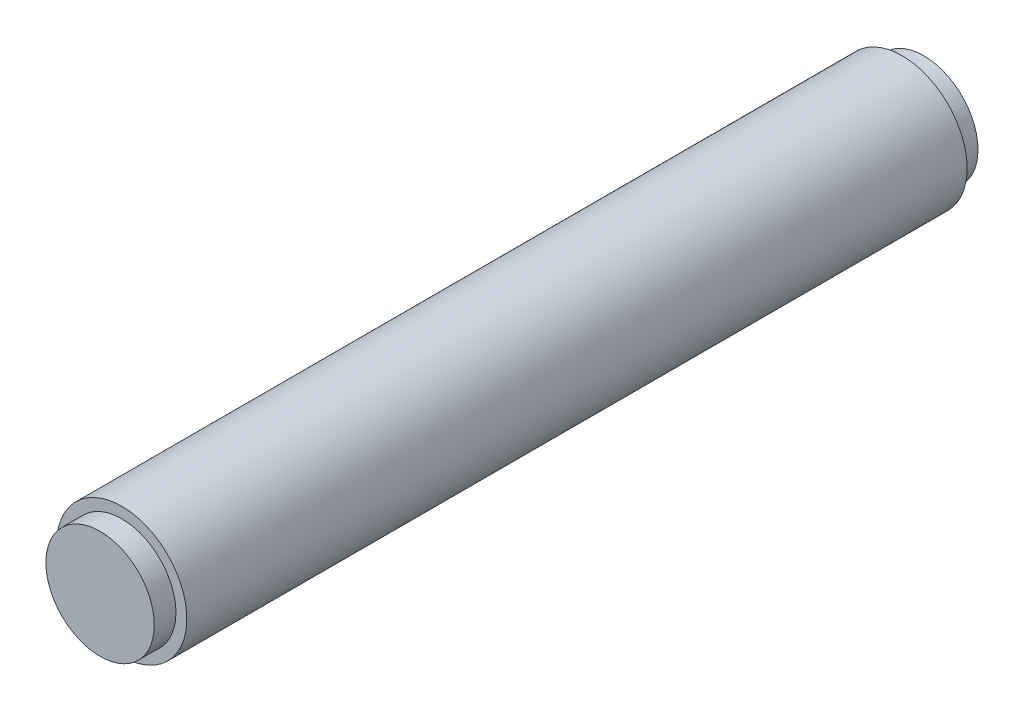
SolidWorks part; units mm, degrees
ref_plane "Alzado" through (0, 0, 0) normal (0, 0, 1) x (1, 0, 0)
ref_plane "Planta" through (0, 0, 0) normal (0, 1, 0) x (1, 0, 0)
ref_plane "Vista lateral" through (0, 0, 0) normal (1, 0, 0) x (0, 0, -1)
sketch "Croquis1" plane through (0, 0, 0) normal (0, 0, 1) x (1, 0, 0)
  circle A0 centre (-60.8092, 26.7675) radius 30
extrude "Saliente-Extruir1" add sketch "Croquis1" along normal blind 360
sketch "Croquis2" plane through (0, 0, 360) normal (0, 0, 1) x (1, 0, 0)
  circle A0 centre (-60.8092, 26.7675) radius 25
extrude "Saliente-Extruir2" add sketch "Croquis2" along normal blind 10
sketch "Croquis3" plane through (0, 0, 0) normal (0, 0, -1) x (-1, 0, 0)
  circle A0 centre (60.8092, 26.7675) radius 25
extrude "Saliente-Extruir3" add sketch "Croquis3" along normal blind 10
